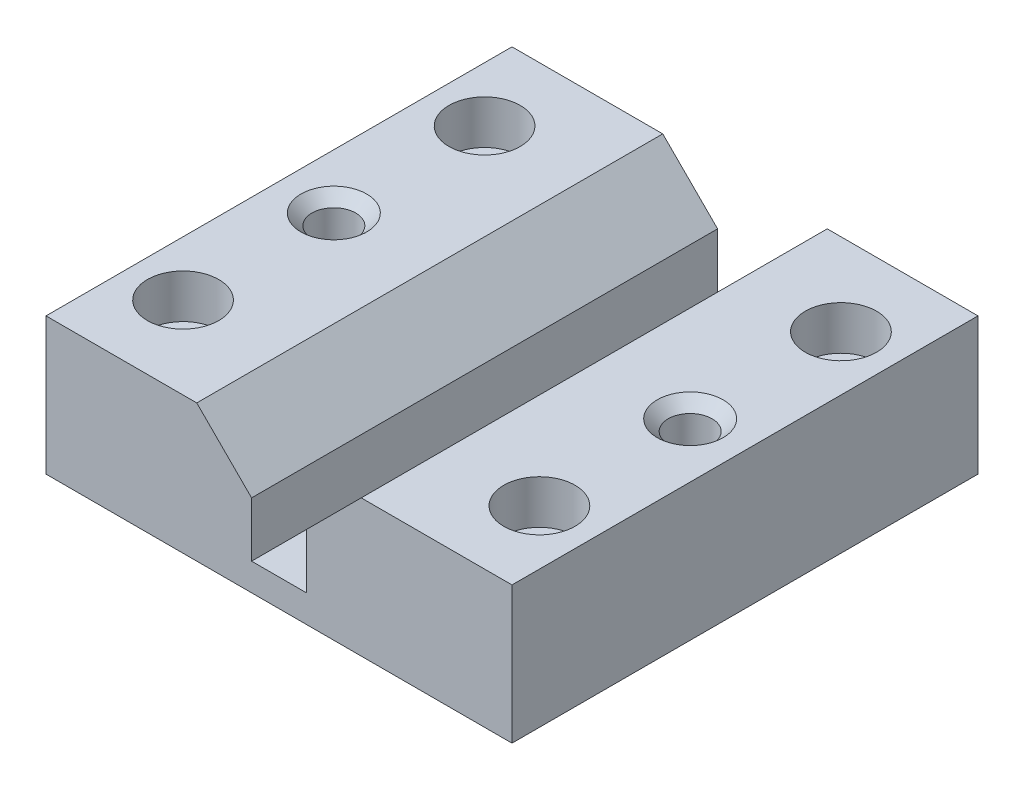
SolidWorks part; units mm, degrees
ref_plane "Спереди" through (0, 0, 0) normal (0, 0, 1) x (1, 0, 0)
ref_plane "Сверху" through (0, 0, 0) normal (0, 1, 0) x (1, 0, 0)
ref_plane "Справа" through (0, 0, 0) normal (1, 0, 0) x (0, 0, -1)
sketch "Эскиз1" plane through (0, 0, 0) normal (0, 0, 1) x (1, 0, 0)
  line L0 (-826.6706, 0) -> (40527.8955, 0) construction
  line L1 (0, -827.0913) -> (0, 40527.4748) construction
  line L2 (42.5, 0) -> (-42.5, 0)
  line L3 (-42.5, 0) -> (-42.5, 25)
  line L4 (-42.5, 25) -> (-15, 25)
  line L5 (-15, 25) -> (-5, 15)
  line L6 (-5, 15) -> (-5, 5)
  line L7 (-5, 5) -> (5, 5)
  line L8 (826.6706, 0) -> (-40527.8955, 0) construction
  line L9 (5, 15) -> (5, 5)
  line L10 (15, 25) -> (5, 15)
  line L11 (42.5, 25) -> (15, 25)
  line L12 (42.5, 0) -> (42.5, 25)
  point P15 (0, 5)
  point P19 (0, 0)
  dimension "D1" = 10
  dimension "D2" = 85
  dimension "D3" = 25
  dimension "D4" = 45
  dimension "D5" = 10
  dimension "D6" = 20
extrude "Бобышка-Вытянуть1" add sketch "Эскиз1" along normal mid plane 85
sketch "Эскиз2" plane through (0, 25, 0) normal (0, 1, 0) x (1, 0, 0)
  line L0 (-32.5, 0) -> (32.5, 0) construction
  line L1 (-32.5, -27.5) -> (32.5, -27.5) construction
  line L2 (-32.5, -27.5) -> (-32.5, 27.5) construction
  line L3 (-32.5, 27.5) -> (32.5, 27.5) construction
  line L4 (32.5, -27.5) -> (32.5, 27.5) construction
  line L5 (-32.5, -27.5) -> (32.5, 27.5) construction
  line L6 (-32.5, 27.5) -> (32.5, -27.5) construction
  circle A0 centre (-32.5, 27.5) radius 6.5
  circle A1 centre (-32.5, -27.5) radius 6.5
  circle A2 centre (32.5, -27.5) radius 6.5
  circle A3 centre (32.5, 27.5) radius 6.5
  point P0 (0, 0)
  dimension "D3" = 13
  dimension "D1" = 55
  dimension "D2" = 65
extrude "Вырез-Вытянуть1" cut sketch "Эскиз2" against normal blind 8
sketch "Эскиз3" plane through (0, 25, 0) normal (0, 1, 0) x (1, 0, 0)
  circle A0 centre (-32.5, 0) radius 4
  circle A1 centre (-32.5, 27.5) radius 4
  circle A2 centre (32.5, 27.5) radius 4
  circle A3 centre (32.5, 0) radius 4
  circle A4 centre (32.5, -27.5) radius 4
  circle A5 centre (-32.5, -27.5) radius 4
  dimension "D1" = 8
extrude "Вырез-Вытянуть2" cut sketch "Эскиз3" against normal through all
chamfer "Фаска1" distance 2 angle 45 2 edges at (-32.5, 25, 4) (32.5, 25, 4)
